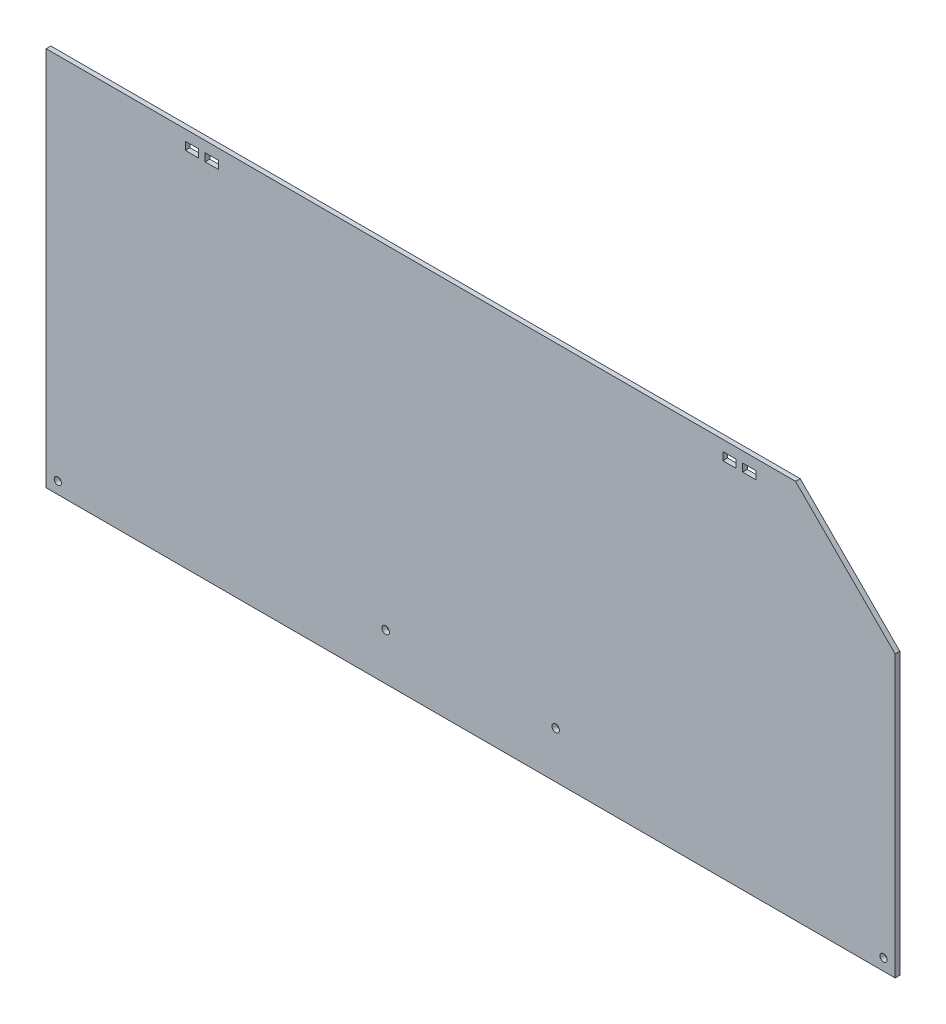
SolidWorks part; units mm, degrees
material "1023 Листовая углеродистая сталь (SS)"
ref_plane "Спереди" through (0, 0, 0) normal (0, 0, 1) x (1, 0, 0)
ref_plane "Сверху" through (0, 0, 0) normal (0, 1, 0) x (1, 0, 0)
ref_plane "Справа" through (0, 0, 0) normal (1, 0, 0) x (0, 0, -1)
sketch "Эскиз1" plane through (0, 0, 0) normal (0, 0, 1) x (1, 0, 0)
  line L40 (-670, 330) -> (-670, 2.45) construction
  line L41 (-25.8343, 657.55) -> (-690, 657.55) construction
  line L42 (0, 660) -> (0, 700) construction
  line L43 (0, 700) -> (-690, 700) construction
  line L44 (-690, -40) -> (-690, 700) construction
  line L45 (-670, 2.45) -> (-25.8343, 2.45) construction
  line L46 (0, 0) -> (0, -40) construction
  line L47 (0, -40) -> (-690, -40) construction
  line L48 (0, 660) -> (40, 620) construction
  line L49 (80, 620) -> (80, 40) construction
  line L50 (40, 40) -> (0, 0) construction
  line L51 (-25.8343, 657.55) -> (60, 571.7157) construction
  line L52 (60, 330) -> (60, 88.2843) construction
  line L53 (60, 88.2843) -> (-25.8343, 2.45) construction
  line L54 (40, 620) -> (80, 620) construction
  line L55 (40, 40) -> (80, 40) construction
  line L56 (-670, 330) -> (60, 330) construction
  line L57 (-669.5, 2.95) -> (-26.0414, 2.95)
  line L58 (59.5, 88.4914) -> (-26.0414, 2.95)
  line L59 (59.5, 329.5) -> (59.5, 88.4914)
  line L60 (-669.5, 329.5) -> (59.5, 329.5)
  line L61 (-669.5, 329.5) -> (-669.5, 2.95)
  point P8 (59.3471, 506.4878)
  point P9 (59.3471, 73.2635)
  point P12 (-689.6529, -12.2779)
  point P13 (-689.6529, 592.3221)
  point P14 (-690.1529, 289.2721)
  point P15 (59.8471, 289.2721)
  point P23 (-690, 330)
  dimension "D1" = 690
  dimension "D2" = 42.45
  dimension "D3" = 42.45
  dimension "D4" = 740
  dimension "D5" = 80
  dimension "D6" = 40
  dimension "D7" = 40
  dimension "D8" = 45
  dimension "D9" = 45
  dimension "D10" = 20
  dimension "D11" = 20
  dimension "D12" = 20
  dimension "D13" = 40
  dimension "D14" = 40
  dimension "D15" = 20
  dimension "D16" = 0.5
extrude "Бобышка-Вытянуть1" add sketch "Эскиз1" along normal blind 4
sketch "Эскиз2" plane through (0, 0, 0) normal (0, 0, -1) x (-1, 0, 0)
  line L6 (669.5, 2.95) -> (26.0414, 2.95) construction
  line L7 (60.5, 12.52) -> (71, 12.52) construction
  line L8 (60.5, 12.52) -> (60.5, 18.32) construction
  line L11 (60.5, 18.32) -> (71, 18.32) construction
  line L12 (71, 12.52) -> (71, 18.32) construction
  line L13 (77.5, 12.52) -> (88, 12.52) construction
  line L15 (77.5, 12.52) -> (77.5, 18.32) construction
  line L20 (77.5, 18.32) -> (88, 18.32) construction
  line L21 (88, 12.52) -> (88, 18.32) construction
  line L22 (-79.5, 77.6119) -> (-79.5, 50077.6119) construction
  line L42 (-59.5, 88.4914) -> (-59.5, 329.5) construction
  line L43 (305, 304.5) -> (305, -49695.5) construction
  line L44 (-59.5, 329.5) -> (669.5, 329.5) construction
  line L53 (71.5, 12.02) -> (71.5, 18.82)
  line L54 (60, 18.82) -> (71.5, 18.82)
  line L55 (60, 12.02) -> (60, 18.82)
  line L56 (60, 12.02) -> (71.5, 12.02)
  line L57 (77, 12.02) -> (77, 18.82)
  line L58 (77, 18.82) -> (88.5, 18.82)
  line L59 (88.5, 12.02) -> (88.5, 18.82)
  line L60 (77, 12.02) -> (88.5, 12.02)
  line L61 (522, 12.52) -> (522, 18.32) construction
  line L62 (532.5, 18.32) -> (522, 18.32) construction
  line L63 (532.5, 12.52) -> (532.5, 18.32) construction
  line L64 (532.5, 12.52) -> (522, 12.52) construction
  line L65 (539, 12.52) -> (539, 18.32) construction
  line L66 (549.5, 18.32) -> (539, 18.32) construction
  line L67 (549.5, 12.52) -> (549.5, 18.32) construction
  line L68 (549.5, 12.52) -> (539, 12.52) construction
  line L69 (533, 12.02) -> (521.5, 12.02)
  line L70 (521.5, 12.02) -> (521.5, 18.82)
  line L71 (533, 18.82) -> (521.5, 18.82)
  line L72 (533, 12.02) -> (533, 18.82)
  line L73 (550, 12.02) -> (538.5, 12.02)
  line L74 (550, 12.02) -> (550, 18.82)
  line L75 (550, 18.82) -> (538.5, 18.82)
  line L76 (538.5, 12.02) -> (538.5, 18.82)
  point P18 (305, 329.5)
  dimension "D1" = 9.57
  dimension "D2" = 10.5
  dimension "D3" = 6.5
  dimension "D4" = 10.5
  dimension "D5" = 5.8
  dimension "D6" = 20
  dimension "D7" = 140
  dimension "D8" = 0.5
extrude "Вырез-Вытянуть1" cut sketch "Эскиз2" against normal through all
sketch "Эскиз3" plane through (0, 0, 0) normal (0, 0, -1) x (-1, 0, 0)
  line L0 (305, 304.5) -> (305, -49695.5) construction
  line L1 (-59.5, 329.5) -> (669.5, 329.5) construction
  circle A0 centre (232, 289.5) radius 3.25
  circle A1 centre (378, 289.5) radius 3.25
  point P9 (305, 329.5)
  dimension "D1" = 6.5
  dimension "D2" = 6.5
  dimension "D3" = 146
  dimension "D5" = 40
  dimension "D4" = 73
extrude "Вырез-Вытянуть2" cut sketch "Эскиз3" against normal through all
sketch "Эскиз4" plane through (0, 0, 0) normal (0, 0, -1) x (-1, 0, 0)
  line L0 (-59.5, 329.5) -> (669.5, 329.5) construction
  line L1 (-59.5, 88.4914) -> (-59.5, 329.5) construction
  line L2 (669.5, 329.5) -> (669.5, 2.95) construction
  circle A0 centre (-49.5, 319.5) radius 3.1
  circle A1 centre (659.5, 319.5) radius 3.1
  dimension "D1" = 6.2
  dimension "D4" = 6.2
  dimension "D2" = 10
  dimension "D3" = 10
  dimension "D5" = 10
  dimension "D6" = 10
extrude "Вырез-Вытянуть3" cut sketch "Эскиз4" against normal through all
mirror "Зеркальное отражение1" about plane through (0, 0, 0) normal (0, 1, 0) of bodies 110 105
delete or keep bodies "Тело-Удалить/Сохранить 1" type delete bodies bodies 110
